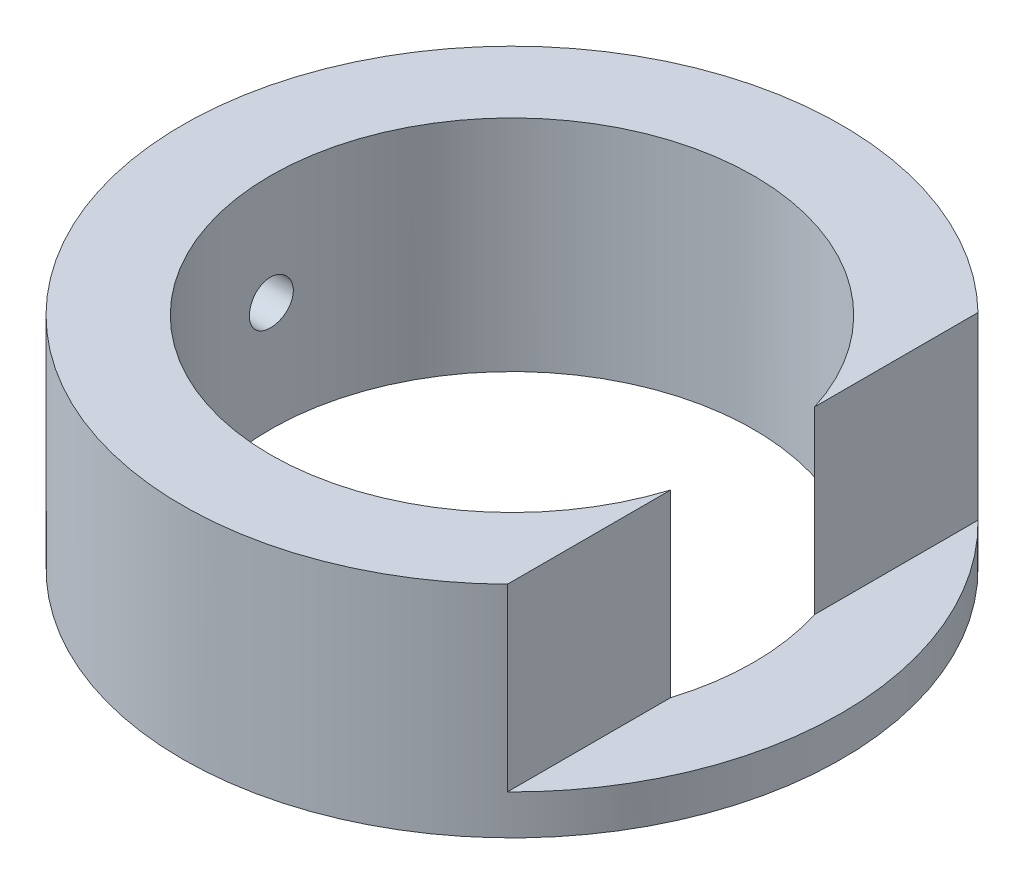
SolidWorks part; units mm, degrees
material "Gray Cast Iron"
ref_plane "Front Plane" through (0, 0, 0) normal (0, 0, 1) x (1, 0, 0)
ref_plane "Top Plane" through (0, 0, 0) normal (0, 1, 0) x (1, 0, 0)
ref_plane "Right Plane" through (0, 0, 0) normal (1, 0, 0) x (0, 0, -1)
sketch "Sketch1" plane through (0, 0, 0) normal (0, 1, 0) x (1, 0, 0)
  circle A0 centre (0, 0) radius 24
  dimension "D1" = 48
extrude "Boss-Extrude1" add sketch "Sketch1" along normal mid plane 16
sketch "Sketch2" plane through (0, 0, 0) normal (0, 1, 0) x (1, 0, 0)
  circle A0 centre (0, 0) radius 17.6
  dimension "D1" = 35.2
extrude "Cut-Extrude1" cut sketch "Sketch2" against normal mid plane 32
sketch "Sketch3" plane through (0, 0, 0) normal (0, 1, 0) x (1, 0, 0)
  line L0 (16.8, -48) -> (27, -48)
  line L1 (27, -48) -> (27, 48)
  line L2 (27, 48) -> (16.8, 48)
  line L3 (16.8, 48) -> (16.8, -48)
extrude "Cut-Extrude2" cut sketch "Sketch3" along normal blind 15.1 from offset 5.1
sketch "Sketch4" plane through (0, 0, 0) normal (1, 0, 0) x (0, 0, -1)
  circle A0 centre (0, 0) radius 1.6
  dimension "D1" = 3.2
extrude "Cut-Extrude3" cut sketch "Sketch4" against normal mid plane 120
